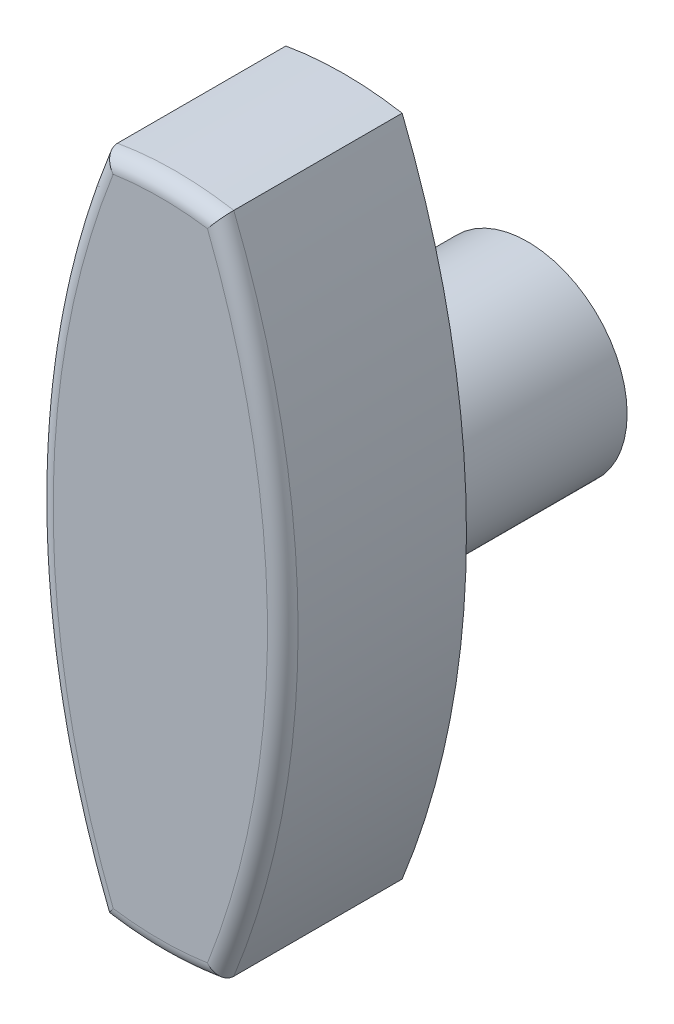
SolidWorks part; units mm, degrees
ref_plane "Front Plane" through (0, 0, 0) normal (0, 0, 1) x (1, 0, 0)
ref_plane "Top Plane" through (0, 0, 0) normal (0, 1, 0) x (1, 0, 0)
ref_plane "Right Plane" through (0, 0, 0) normal (1, 0, 0) x (0, 0, -1)
sketch "Sketch1" plane through (0, 0, 0) normal (0, 0, 1) x (1, 0, 0)
  line L0 (-2.6458, -3) -> (2.6458, -3)
  circle A0 centre (0, 0) radius 4 construction
  arc A1 (-2.6458, -3) -> (2.6458, -3) centre (0, 0) cw
  circle A2 centre (0, 0) radius 6.5
  dimension "D1" = 8
  dimension "D3" = 13
  dimension "D2" = 3
extrude "Boss-Extrude1" add sketch "Sketch1" along normal blind 12
sketch "Sketch2" plane through (0, 0, 12) normal (0, 0, 1) x (1, 0, 0)
  line L0 (0, 0) -> (-46.4693, 0) construction
  line L1 (0, 0) -> (0, 22) construction
  circle A0 centre (0, 0) radius 22 construction
  arc A1 (3.8, 21.6693) -> (3.8, -21.6693) centre (-50, 0) cw
  arc A2 (3.8, 21.6693) -> (-3.8, 21.6693) centre (0, 0) ccw
  arc A3 (3.8, -21.6693) -> (-3.8, -21.6693) centre (0, 0) cw
  arc A4 (-3.8, 21.6693) -> (-3.8, -21.6693) centre (50, 0) ccw
  dimension "D1" = 44
  dimension "D3" = 58
  dimension "D2" = 50
extrude "Boss-Extrude2" add sketch "Sketch2" along normal blind 12
fillet "Fillet1" radius 1 4 edges at (8, 0, 24) (0, -22, 24) (-8, 0, 24) (0, 22, 24)
